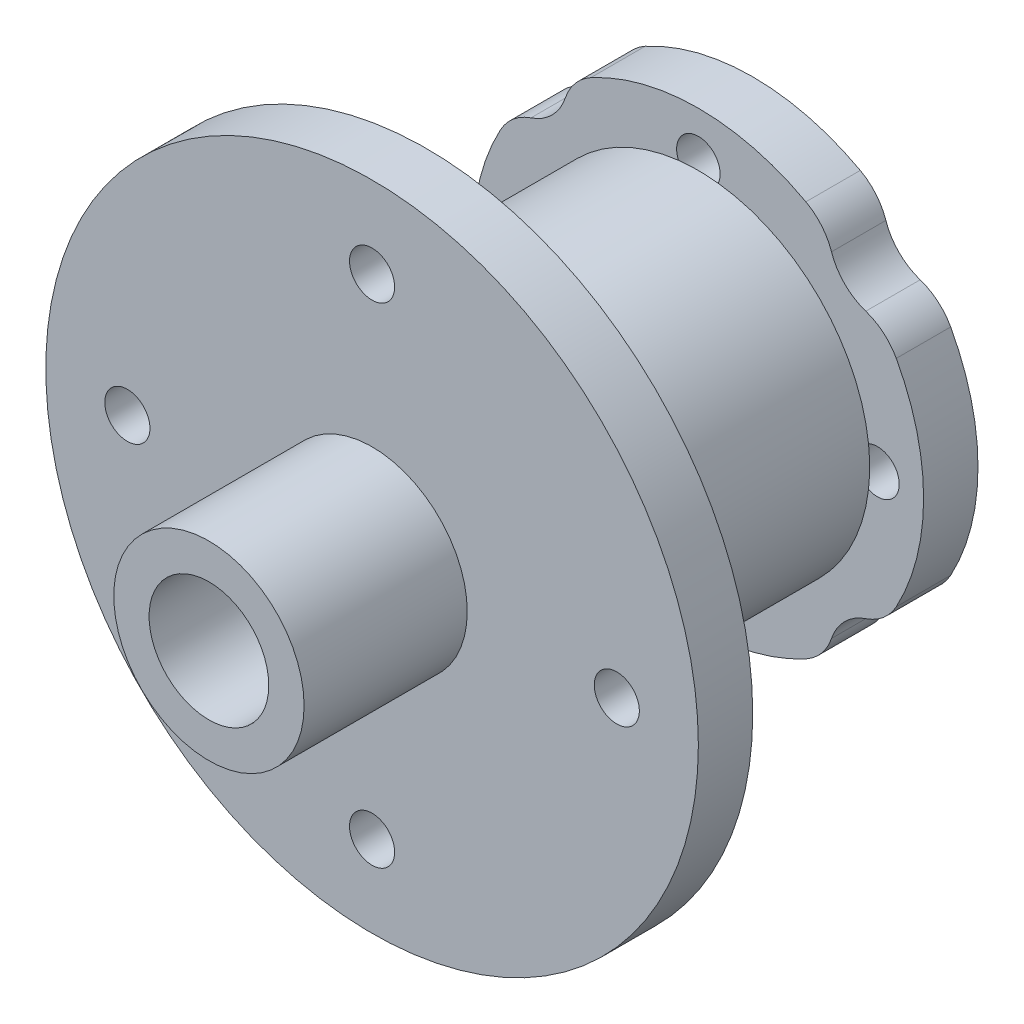
SolidWorks part; units mm, degrees
ref_plane "Front Plane" through (0, 0, 0) normal (0, 0, 1) x (1, 0, 0)
ref_plane "Top Plane" through (0, 0, 0) normal (0, 1, 0) x (1, 0, 0)
ref_plane "Right Plane" through (0, 0, 0) normal (1, 0, 0) x (0, 0, -1)
sketch "Sketch1" plane through (0, 0, 0) normal (0, 0, 1) x (1, 0, 0)
  line L0 (0, 41.42) -> (0, 32.935) construction
  line L1 (-41.42, 0) -> (-36.935, 0) construction
  line L2 (25, 33.0245) -> (25, -33.0245)
  line L3 (-33.0245, 25) -> (33.0245, 25)
  line L4 (-25, 33.0245) -> (-25, -33.0245)
  line L5 (-33.0245, -25) -> (33.0245, -25)
  line L6 (-41.42, -25) -> (41.42, -25) construction
  line L7 (-41.42, 25) -> (41.42, 25) construction
  line L8 (-25, 41.42) -> (-25, -41.42) construction
  line L9 (25, 41.42) -> (25, -41.42) construction
  line L10 (0, -28.935) -> (0, -32.935) construction
  line L11 (0, 41.42) -> (0, -41.42) construction
  line L12 (0, -36.935) -> (0, -41.42) construction
  line L13 (36.935, 0) -> (41.42, 0) construction
  line L14 (-41.42, 0) -> (41.42, 0) construction
  line L15 (0, 28.935) -> (0, -25) construction
  line L16 (-32.935, 0) -> (32.935, 0) construction
  arc A0 (-33.0245, 25) -> (-33.0245, -25) centre (0, 0) ccw
  circle A2 centre (0, 32.935) radius 4
  circle A3 centre (32.935, 0) radius 4
  circle A4 centre (0, -32.935) radius 4
  circle A5 centre (-32.935, 0) radius 4
  arc A6 (-25, -33.0245) -> (25, -33.0245) centre (0, 0) ccw
  arc A8 (33.0245, -25) -> (33.0245, 25) centre (0, 0) ccw
  arc A10 (25, 33.0245) -> (-25, 33.0245) centre (0, 0) ccw
  point P19 (0, 0)
  dimension "D1" = 65.87
  dimension "D2" = 82.84
  dimension "D3" = 8
  dimension "D5" = 25
  dimension "D6" = 25
  dimension "D7" = 25
  dimension "D8" = 25
  dimension "D4" = 4
extrude "Boss-Extrude1" add sketch "Sketch1" along normal blind 10 contours L4 L5 L2 L3 | L3 A0 L5 L4 A5 | L2 A10 L4 L3 A2 | L5 A8 L3 L2 A3 | L4 A6 L2 L5 A4
fillet "Fillet1" radius 10 8 edges at (-33.0245, 25, 5) (-33.0245, -25, 5) (-25, -33.0245, 5) (25, -33.0245, 5) (33.0245, -25, 5) (33.0245, 25, 5) (25, 33.0245, 5) (-25, 33.0245, 5)
fillet "Fillet2" radius 10 4 edges at (25, 25, 5) (-25, 25, 5) (-25, -25, 5) (25, -25, 5)
sketch "Sketch2" plane through (0, 0, 10) normal (0, 0, 1) x (1, 0, 0)
  circle A0 centre (0, 0) radius 31.5
  dimension "D1" = 63
extrude "Boss-Extrude2" add sketch "Sketch2" along normal blind 50
sketch "Sketch3" plane through (0, 0, 60) normal (0, 0, 1) x (1, 0, 0)
  line L0 (0, 60) -> (0, -60) construction
  line L1 (-60, 0) -> (60, 0) construction
  circle A7 centre (0, 0) radius 60
  circle A8 centre (0, 0) radius 45
  circle A9 centre (0, 45) radius 4.15
  circle A10 centre (45, 0) radius 4.15
  circle A11 centre (0, -45) radius 4.15
  circle A12 centre (-45, 0) radius 4.15
  point P18 (0, 0)
  point P22 (0, 0)
  dimension "D1" = 90
  dimension "D2" = 120
  dimension "D4" = 4
  dimension "D3" = 8.3
extrude "Boss-Extrude3" add sketch "Sketch3" along normal blind 10
sketch "Sketch4" plane through (0, 0, 70) normal (0, 0, 1) x (1, 0, 0)
  circle A0 centre (0, 0) radius 17.5
  circle A1 centre (0, 0) radius 11
  dimension "D1" = 35
  dimension "D2" = 22
extrude "Boss-Extrude4" add sketch "Sketch4" along normal blind 30
